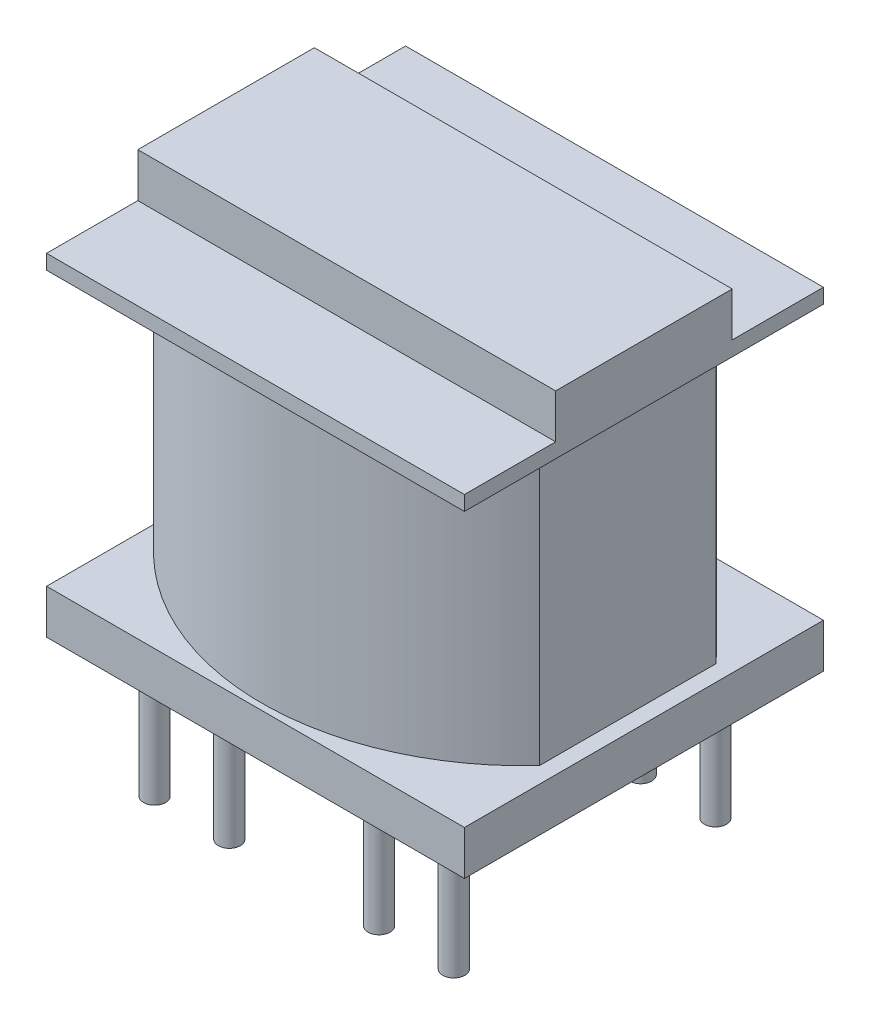
SolidWorks part; units mm, degrees
ref_plane "前视基准面" through (0, 0, 0) normal (0, 0, 1) x (1, 0, 0)
ref_plane "上视基准面" through (0, 0, 0) normal (0, 1, 0) x (1, 0, 0)
ref_plane "右视基准面" through (0, 0, 0) normal (1, 0, 0) x (0, 0, -1)
sketch "草图1" plane through (0, 0, 0) normal (0, 1, 0) x (1, 0, 0)
  line L0 (-11.8777, 0) -> (12.8033, 0) construction
  line L1 (-7.1, 6.1) -> (7.1, 6.1)
  line L2 (-7.1, 6.1) -> (-7.1, -6.1)
  line L3 (-7.1, -6.1) -> (7.1, -6.1)
  line L4 (7.1, 6.1) -> (7.1, -6.1)
  line L5 (0, 8.8277) -> (0, -10.3332) construction
  dimension "D1" = 14.2
  dimension "D2" = 12.2
extrude "凸台-拉伸1" add sketch "草图1" along normal blind 12.8
sketch "草图2" plane through (0, 12.8, 0) normal (0, 1, 0) x (1, 0, 0)
  line L0 (-11.9405, 0) -> (12.0392, 0) construction
  line L1 (-10.1889, 3) -> (9.5475, 3)
  line L2 (-10.1889, 3) -> (-10.1889, -3)
  line L3 (-10.1889, -3) -> (9.5475, -3)
  line L4 (9.5475, 3) -> (9.5475, -3)
  dimension "D1" = 6
extrude "切除-拉伸1" cut sketch "草图2" against normal blind 1.5 flip side to cut
ref_plane "基准面1" through (0, 1.5, 0) normal (0, 1, 0) x (1, 0, 0)
sketch "草图3" plane through (0, 1.5, 0) normal (0, 1, 0) x (1, 0, 0)
  line L0 (0, 7.8644) -> (0, -8.6134) construction
  line L1 (-7.1, -3) -> (7.1, -3) construction
  line L2 (-6.5542, 3) -> (-6.5542, -3)
  line L3 (7.1, 3) -> (-7.1, 3) construction
  line L4 (7.1, 3) -> (-7.1, 3) construction
  line L5 (6.5542, 3) -> (6.5542, -3)
  line L6 (-9.6629, 0) -> (11.6907, 0) construction
  arc A0 (-6.5542, 3) -> (6.5542, 3) centre (0, -3) cw
  arc A1 (-6.5542, -3) -> (6.5542, -3) centre (0, 3) ccw
extrude "切除-拉伸2" cut sketch "草图3" along normal offset from surface (9.3 mm away) 0.5 flip side to cut up to face at (0, 11.3, 4.55)
sketch "草图4" plane through (0, 0, 0) normal (0, -1, 0) x (1, 0, 0)
  line L0 (-14.72, 0) -> (16.1596, 0) construction
  line L1 (0, 9.6567) -> (0, -9.9738) construction
  line L2 (-5.085, 7.8922) -> (-5.085, -7.5476) construction
  line L3 (-8.5406, 4.445) -> (11.1635, 4.445) construction
  line L4 (-8.5406, -4.445) -> (11.1635, -4.445) construction
  line L5 (5.085, 7.8922) -> (5.085, -7.5476) construction
  circle A0 centre (-5.085, 4.445) radius 0.375
  circle A1 centre (-2.545, 4.445) radius 0.375
  circle A2 centre (2.545, 4.445) radius 0.375
  circle A3 centre (5.085, 4.445) radius 0.375
  circle A4 centre (5.085, -4.445) radius 0.375
  circle A5 centre (2.545, -4.445) radius 0.375
  circle A6 centre (-2.545, -4.445) radius 0.375
  circle A7 centre (-5.085, -4.445) radius 0.375
  dimension "D1" = 0.75
  dimension "D5" = 0.75
  dimension "D2" = 10.17
  dimension "D3" = 8.89
  dimension "D4" = 2.54
extrude "凸台-拉伸2" add sketch "草图4" along normal blind 4.5
